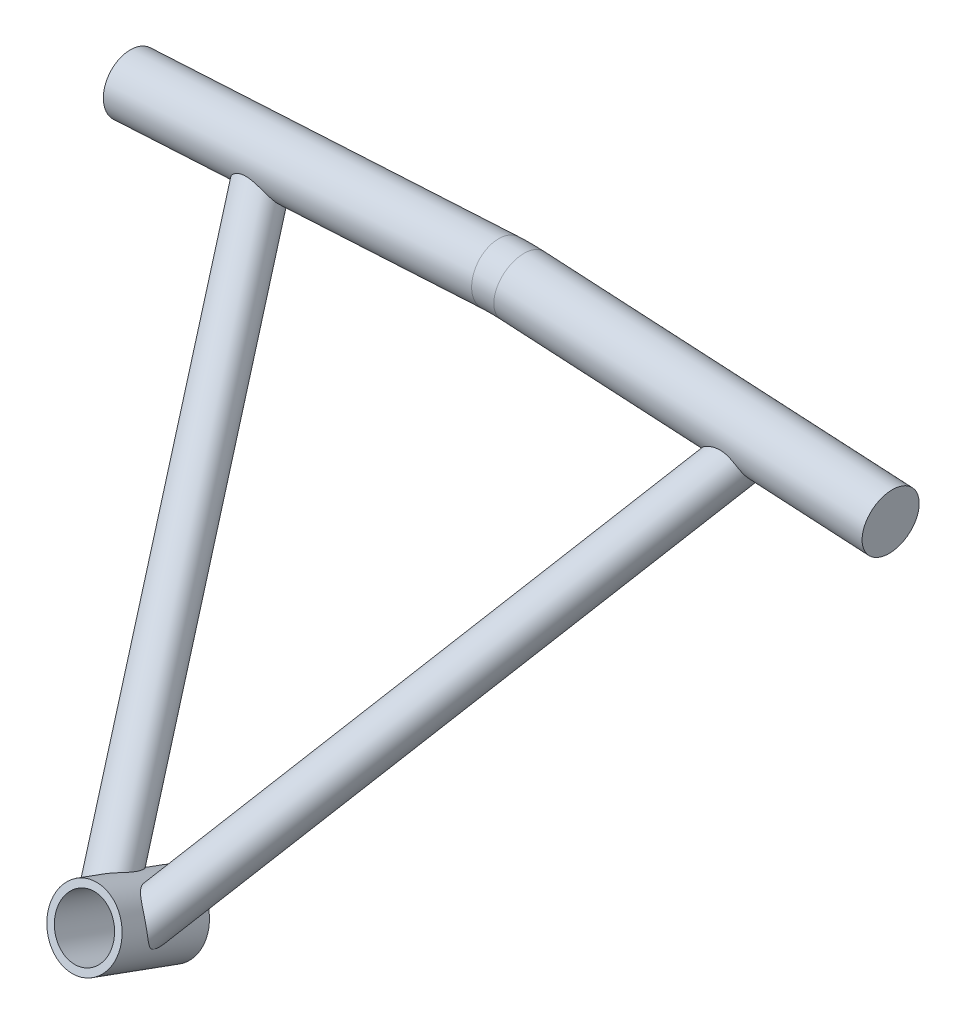
SolidWorks part; units mm, degrees
material "AISI 4130 Steel, normalized at 870C"
ref_plane "Front Plane" through (0, 0, 0) normal (0, 0, 1) x (1, 0, 0)
ref_plane "Top Plane" through (0, 0, 0) normal (0, 1, 0) x (1, 0, 0)
ref_plane "Right Plane" through (0, 0, 0) normal (1, 0, 0) x (0, 0, -1)
sketch "Sketch3" plane through (0, 0, 0) normal (0, 1, 0) x (1, 0, 0)
  line L0 (-5.08, -6.35) -> (5.08, -6.35) construction
  line L2 (0, -88.2205) -> (0, 88.2205) construction
  line L3 (5.08, 0) -> (-5.08, 0) construction
  dimension "D1" = 5.08
  dimension "D2" = 10.16
  dimension "D3" = 6.35
  dimension "D4" = 10.16
  dimension "D5" = 5.08
ref_plane "Plane1" through (0, 3.1441, 2.7331) normal (0, 0.7547, 0.6561) x (1, 0, 0)
ref_plane "Plane3" through (0, 0, 0) normal (0, 0.342, 0.9397) x (-1, 0, 0)
sketch "Sketch1" plane through (0, 0, 0) normal (0, 0.342, 0.9397) x (1, 0, 0)
  circle A0 centre (0, 0) radius 15.875
  dimension "D1" = 31.75
extrude "Boss-Extrude1" add sketch "Sketch1" along normal mid plane 41.402 contours A0
sketch "Sketch4" plane through (0, 3.1441, 2.7331) normal (0, 0.7547, 0.6561) x (1, 0, 0)
  line L0 (-5.08, -4.7924) -> (-106.5832, 223.1874)
  line L2 (0, -24.1976) -> (0, 24.1976) construction
  dimension "D2" = 24
  dimension "D3" = 249.555
sweep "Sweep1" add path "Sketch4" circular profile diameter 19.05 parameters "D3"=19.05
sketch "Sketch15" plane through (0, 3.1441, 2.7331) normal (0, 0.7547, 0.6561) x (1, 0, 0)
  line L0 (5.08, -4.7924) -> (107.0997, 224.3476)
  line L1 (0, -96.8803) -> (0, 96.8803) construction
  dimension "D1" = 250.825
  dimension "D2" = 24
sweep "Sweep2" add path "Sketch15" circular profile diameter 19.05 parameters "D3"=19.05
sketch "Sketch2" plane through (0, -7.0802, -19.4526) normal (0, -0.342, -0.9397) x (-1, 0, 0)
  circle A0 centre (0, 0) radius 12.7
  dimension "D1" = 25.4
extrude "Cut-Extrude1" cut sketch "Sketch2" against normal up to next
sketch "Sketch36" plane through (-100.5628, 148.1826, -170.4646) normal (-0.4067, 0.5993, -0.6895) x (0.9117, 0.3145, -0.2644)
  circle A0 centre (-6.3105, -4.5784) radius 7.9375
  dimension "D1" = 15.875
extrude "Cut-Extrude2" cut sketch "Sketch36" against normal blind 127
sketch "Sketch37" plane through (101.0794, 148.9438, -171.3402) normal (0.4067, 0.5993, -0.6895) x (0.9117, -0.3145, 0.2644)
  circle A0 centre (6.3105, -4.5784) radius 7.9375
  dimension "D1" = 15.875
extrude "Cut-Extrude3" cut sketch "Sketch37" against normal blind 127
ref_plane "Plane2" through (0, 0, -170.688) normal (0, 0, 1) x (1, 0, 0)
sketch "Sketch40" plane through (-106.934, 0, -170.688) normal (0, 0, 1) x (1, 0, 0)
  line L2 (106.934, -101.4769) -> (106.934, 101.4769) construction
  line L3 (101.9947, 162.4227) -> (-62.0894, 153.292)
  line L4 (111.8733, 162.4227) -> (275.9574, 153.292)
  arc A0 (101.9947, 162.4227) -> (111.8733, 162.4227) centre (106.934, 73.66) cw
  point P0 (106.934, 162.56)
  point P7 (106.934, 162.56)
  dimension "D1" = 164.338
  dimension "D3" = 88.9
  dimension "D2" = 164.338
  dimension "D4" = 9.8786
sweep "Sweep3" add path "Sketch40" circular profile diameter 25.4 parameters "D3"=25.4
